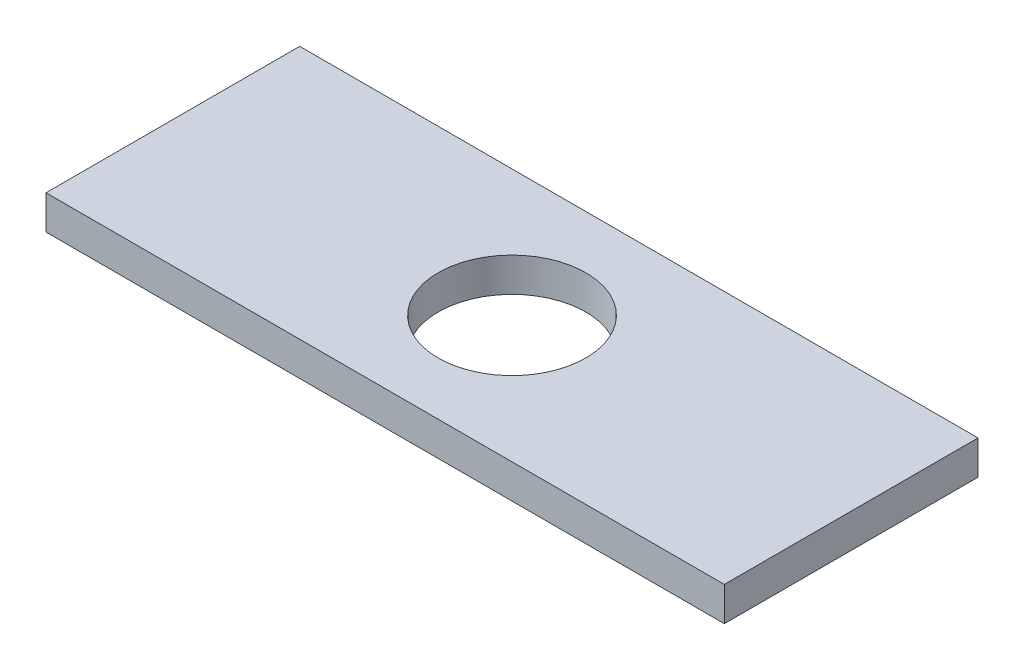
SolidWorks part; units mm, degrees
material "AISI 316 Stainless Steel Sheet (SS)"
ref_plane "Front Plane" through (0, 0, 0) normal (0, 0, 1) x (1, 0, 0)
ref_plane "Top Plane" through (0, 0, 0) normal (0, 1, 0) x (1, 0, 0)
ref_plane "Right Plane" through (0, 0, 0) normal (1, 0, 0) x (0, 0, -1)
sketch "Sketch3" plane through (0, 0, 0) normal (0, 1, 0) x (1, 0, 0)
  line L1 (-149.4991, 55.9102) -> (149.4991, 55.9102)
  line L2 (-149.4991, 55.9102) -> (-149.4991, -55.9102)
  line L3 (-149.4991, -55.9102) -> (149.4991, -55.9102)
  line L4 (149.4991, 55.9102) -> (149.4991, -55.9102)
  line L5 (-149.4991, 55.9102) -> (149.4991, -55.9102) construction
  line L6 (-149.4991, -55.9102) -> (149.4991, 55.9102) construction
  point P0 (0, 0)
extrude "Boss-Extrude2" add sketch "Sketch3" along normal blind 15
sketch "Sketch4" plane through (0, 15, 0) normal (0, 1, 0) x (1, 0, 0)
  circle A0 centre (0, 0) radius 32.55
  dimension "D1" = 65.1
extrude "Cut-Extrude1" cut sketch "Sketch4" against normal blind 15
